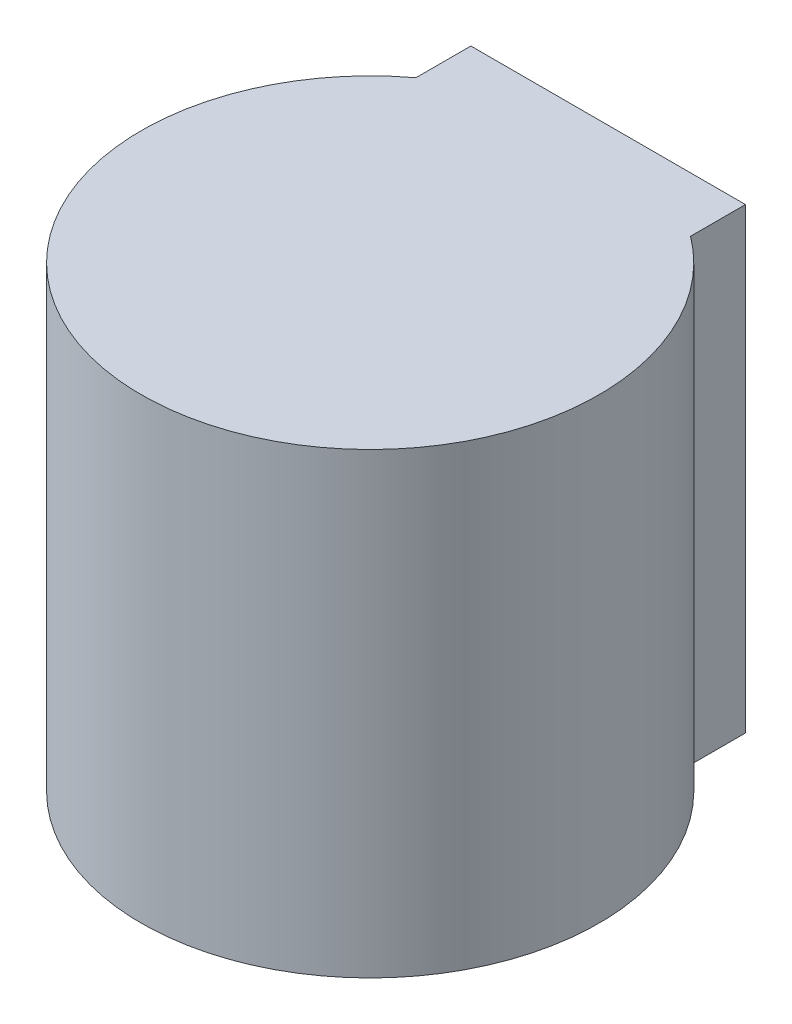
SolidWorks part; units mm, degrees
ref_plane "Спереди" through (0, 0, 0) normal (0, 0, 1) x (1, 0, 0)
ref_plane "Сверху" through (0, 0, 0) normal (0, 1, 0) x (1, 0, 0)
ref_plane "Справа" through (0, 0, 0) normal (1, 0, 0) x (0, 0, -1)
sketch "Эскиз1" plane through (0, 0, 0) normal (0, 1, 0) x (1, 0, 0)
  circle A0 centre (0, 0) radius 250
  dimension "D1" = 500
extrude "Бобышка-Вытянуть1" add sketch "Эскиз1" along normal blind 500
sketch "Эскиз2" plane through (0, 0, 0) normal (0, 0, 1) x (1, 0, 0)
  line L0 (250, 500) -> (-250, 500) construction
  line L1 (-150, 500) -> (150, 500)
  line L2 (-150, 500) -> (-150, 0)
  line L3 (-150, 0) -> (150, 0)
  line L4 (150, 500) -> (150, 0)
  line L5 (-250, 500) -> (-250, 0) construction
  dimension "D1" = 100
extrude "Бобышка-Вытянуть2" add sketch "Эскиз2" against normal blind 260
